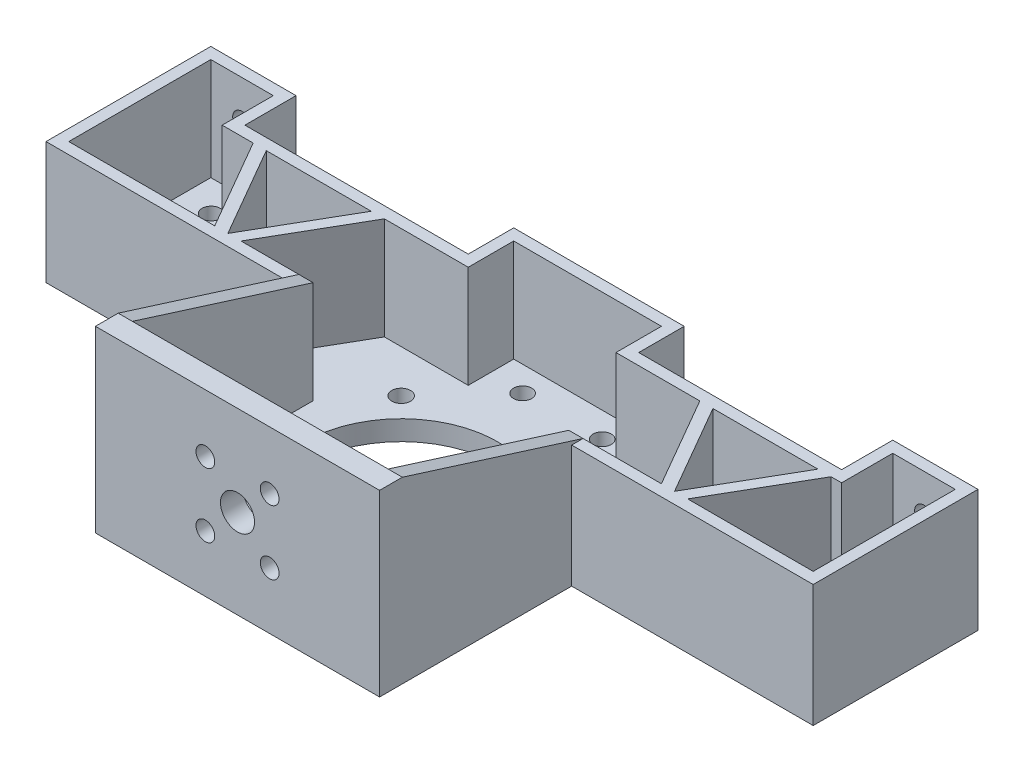
SolidWorks part; units mm, degrees
ref_plane "前视基准面" through (0, 0, 0) normal (0, 0, 1) x (1, 0, 0)
ref_plane "上视基准面" through (0, 0, 0) normal (0, 1, 0) x (1, 0, 0)
ref_plane "右视基准面" through (0, 0, 0) normal (1, 0, 0) x (0, 0, -1)
sketch "草图2" plane through (0, 0, 0) normal (0, 1, 0) x (1, 0, 0)
  line L15 (-42.5, 33.8) -> (-42.5, 62.8)
  line L16 (-42.5, 62.8) -> (-27.5, 62.8)
  line L17 (-27.5, 62.8) -> (-27.5, 53.8)
  line L18 (-27.5, 53.8) -> (11.8, 53.8)
  line L19 (11.8, 53.8) -> (11.8, 61.8)
  line L20 (11.8, 61.8) -> (41.8, 61.8)
  line L21 (41.8, 61.8) -> (41.8, 53.8)
  line L22 (41.8, 53.8) -> (77.5, 53.8)
  line L23 (77.5, 53.8) -> (77.5, 62.8)
  line L24 (77.5, 62.8) -> (92.5, 62.8)
  line L25 (92.5, 62.8) -> (92.5, 33.8)
  line L27 (-42.5, 33.8) -> (0, 33.8)
  line L28 (0, 33.8) -> (0, 0)
  line L29 (0, 0) -> (50, 0)
  line L30 (50, 0) -> (50, 33.8)
  line L31 (50, 33.8) -> (92.5, 33.8)
  line L32 (25, -43.9837) -> (25, 32.7782) construction
  line L33 (85, 58.3) -> (85, -14.8283) construction
  line L34 (-35, 58.3) -> (-35, -33.736) construction
  line L35 (26.8, 66.1921) -> (26.8, -26.5769) construction
  circle A1 centre (-35, 55.365) radius 1.6
  circle A3 centre (85, 55.365) radius 1.6
  circle A6 centre (19.8, 55.365) radius 1.6
  circle A7 centre (33.8, 55.365) radius 1.6
  circle A10 centre (25, 28.8) radius 17
  circle A11 centre (40.5, 44.3) radius 1.65
  circle A12 centre (40.5, 13.3) radius 1.65
  circle A13 centre (9.5, 13.3) radius 1.65
  circle A14 centre (9.5, 44.3) radius 1.65
  point P0 (-35, 55.365)
  point P1 (85, 55.365)
  point P2 (85, 58.3)
  point P3 (-35, 58.3)
  point P4 (33.8, 55.365)
  point P6 (19.8, 55.365)
  point P50 (25, 28.8)
  dimension "D2" = 120
  dimension "D22" = 34
  dimension "D7" = 28.8
  dimension "D10" = 50
  dimension "D11" = 25
  dimension "D14" = 3.3
  dimension "D17" = 31
  dimension "D3" = 1
  dimension "D4" = 14
  dimension "D5" = 54.8
  dimension "D8" = 8
  dimension "D9" = 30
  dimension "D12" = 15
  dimension "D13" = 15
  dimension "D15" = 20
  dimension "D16" = 4
  dimension "D18" = 4.5
extrude "凸台-拉伸2" add sketch "草图2" along normal blind 3.5
sketch "草图6" plane through (0, 3.5, 0) normal (0, 1, 0) x (1, 0, 0)
  line L9 (25, 28.8) -> (25, -10.253) construction
  line L12 (11.8, 53.8) -> (-27.5, 53.8) construction
  line L13 (11.8, 61.8) -> (11.8, 53.8) construction
  line L14 (41.8, 61.8) -> (11.8, 61.8) construction
  line L15 (41.8, 53.8) -> (41.8, 61.8) construction
  line L16 (77.5, 53.8) -> (41.8, 53.8) construction
  line L17 (77.5, 62.8) -> (77.5, 53.8) construction
  line L18 (92.5, 62.8) -> (77.5, 62.8) construction
  line L19 (92.5, 33.8) -> (92.5, 62.8) construction
  line L20 (50, 33.8) -> (92.5, 33.8) construction
  line L21 (50, 0) -> (50, 33.8) construction
  line L22 (0, 0) -> (50, 0) construction
  line L23 (0, 33.8) -> (0, 0) construction
  line L24 (-42.5, 33.8) -> (0, 33.8) construction
  line L25 (-42.5, 62.8) -> (-42.5, 33.8) construction
  line L26 (-27.5, 53.8) -> (-27.5, 62.8) construction
  line L27 (-27.5, 62.8) -> (-42.5, 62.8) construction
  line L28 (11.8, 53.8) -> (-27.5, 53.8)
  line L29 (11.8, 61.8) -> (11.8, 53.8)
  line L30 (41.8, 61.8) -> (11.8, 61.8)
  line L31 (41.8, 53.8) -> (41.8, 61.8)
  line L32 (77.5, 53.8) -> (41.8, 53.8)
  line L33 (77.5, 62.8) -> (77.5, 53.8)
  line L34 (92.5, 62.8) -> (77.5, 62.8)
  line L35 (92.5, 33.8) -> (92.5, 62.8)
  line L36 (50, 33.8) -> (92.5, 33.8)
  line L37 (50, 0) -> (50, 33.8)
  line L38 (0, 0) -> (50, 0)
  line L39 (0, 33.8) -> (0, 0)
  line L40 (-42.5, 33.8) -> (0, 33.8)
  line L41 (-42.5, 62.8) -> (-42.5, 33.8)
  line L42 (-27.5, 53.8) -> (-27.5, 62.8)
  line L43 (-27.5, 62.8) -> (-42.5, 62.8)
  line L44 (13.8, 51.8) -> (-29.5, 51.8)
  line L45 (-29.5, 51.8) -> (-29.5, 60.8)
  line L46 (-29.5, 60.8) -> (-40.5, 60.8)
  line L47 (-40.5, 60.8) -> (-40.5, 35.8)
  line L48 (-40.5, 35.8) -> (2.5, 35.8)
  line L49 (2.5, 35.8) -> (2.5, 4)
  line L50 (2.5, 4) -> (47.5, 4)
  line L51 (47.5, 4) -> (47.5, 35.8)
  line L52 (47.5, 35.8) -> (90.5, 35.8)
  line L53 (90.5, 35.8) -> (90.5, 60.8)
  line L54 (90.5, 60.8) -> (79.5, 60.8)
  line L55 (79.5, 60.8) -> (79.5, 51.8)
  line L56 (79.5, 51.8) -> (39.8, 51.8)
  line L57 (39.8, 51.8) -> (39.8, 59.8)
  line L58 (39.8, 59.8) -> (13.8, 59.8)
  line L59 (13.8, 59.8) -> (13.8, 51.8)
  dimension "D1" = 4
  dimension "D2" = 2
  dimension "D3" = 2
  dimension "D4" = 2
  dimension "D5" = 2
  dimension "D6" = 2
  dimension "D7" = 2
  dimension "D8" = 2
  dimension "D9" = 2
  dimension "D10" = 2
  dimension "D11" = 2
  dimension "D12" = 2
  dimension "D13" = 2
  dimension "D14" = 2.5
  dimension "D15" = 2.5
  dimension "D16" = 2
extrude "凸台-拉伸3" add sketch "草图6" along normal blind 18
sketch "草图11" plane through (0, 21.5, 0) normal (0, 1, 0) x (1, 0, 0)
  line L0 (2.5, 35.8) -> (2.5, 4)
  line L1 (2.5, 4) -> (47.5, 4)
  line L2 (47.5, 4) -> (47.5, 35.8)
  line L3 (47.5, 35.8) -> (50, 35.8)
  line L4 (47.5, 35.8) -> (90.5, 35.8) construction
  line L5 (50, 35.8) -> (50, 0)
  line L6 (50, 0) -> (50, 33.8) construction
  line L7 (50, 0) -> (0, 0)
  line L8 (0, 0) -> (0, 35.8)
  line L9 (-40.5, 35.8) -> (2.5, 35.8) construction
  line L10 (0, 35.8) -> (2.5, 35.8)
extrude "凸台-拉伸4" add sketch "草图11" along normal blind 10
sketch "草图12" plane through (0, 0, 0) normal (-1, 0, 0) x (0, 0, 1)
  line L0 (-35.8, 21.5) -> (-4, 31.5)
  line L1 (-35.8, 31.5) -> (0, 31.5) construction
  line L2 (-4, 31.5) -> (-35.8, 31.5)
  line L3 (-35.8, 31.5) -> (-35.8, 21.5)
  line L4 (0, 31.5) -> (0, 0) construction
  dimension "D1" = 4
extrude "切除-拉伸5" cut sketch "草图12" against normal through all
sketch "草图10" plane through (0, 0, 0) normal (0, 0, 1) x (1, 0, 0)
  line L0 (25, 37.2917) -> (25, -8.8083) construction
  line L5 (0, 0) -> (50, 0) construction
  line L6 (0, 31.5) -> (0, 0) construction
  line L7 (50, 31.5) -> (50, 0) construction
  circle A0 centre (25, 15.6569) radius 3
  circle A1 centre (30.6569, 21.3137) radius 1.65
  circle A2 centre (30.6569, 10) radius 1.65
  circle A3 centre (19.3431, 10) radius 1.65
  circle A4 centre (19.3431, 21.3137) radius 1.65
  point P2 (0, 0)
  point P19 (25, 15.6569)
  dimension "D1" = 10
  dimension "D2" = 6
  dimension "D3" = 3.3
  dimension "D4" = 8
  dimension "D5" = 4
extrude "切除-拉伸4" cut sketch "草图10" against normal blind 5
sketch "草图13" plane through (0, 3.5, 0) normal (0, 1, 0) x (1, 0, 0)
  line L0 (-21.7376, 51.8) -> (-12.5, 35.8)
  line L1 (13.8, 51.8) -> (-29.5, 51.8) construction
  line L2 (-40.5, 35.8) -> (0, 35.8) construction
  line L3 (-12.5, 35.8) -> (-3.2624, 51.8)
  line L5 (-21.7376, 51.8) -> (-24.047, 51.8)
  line L6 (13.8, 51.8) -> (-29.5, 51.8) construction
  line L7 (-24.047, 51.8) -> (-14.8094, 35.8)
  line L8 (-27.5, 53.8) -> (-27.5, 62.8) construction
  line L9 (-14.8094, 35.8) -> (-12.5, 35.8)
  line L10 (-3.2624, 51.8) -> (-0.953, 51.8)
  line L11 (-0.953, 51.8) -> (-10.1906, 35.8)
  line L12 (-10.1906, 35.8) -> (-12.5, 35.8)
  line L13 (-12.5, 35.8) -> (-12.5, 56.0294) construction
  line L14 (0, 35.8) -> (0, 4) construction
  line L15 (26.8, 61.8) -> (26.8, -17.4304) construction
  line L16 (41.8, 61.8) -> (11.8, 61.8) construction
  line L17 (63.7906, 35.8) -> (66.1, 35.8)
  line L18 (54.553, 51.8) -> (63.7906, 35.8)
  line L19 (56.8624, 51.8) -> (54.553, 51.8)
  line L20 (66.1, 35.8) -> (56.8624, 51.8)
  line L21 (68.4094, 35.8) -> (66.1, 35.8)
  line L22 (77.647, 51.8) -> (68.4094, 35.8)
  line L23 (75.3376, 51.8) -> (77.647, 51.8)
  line L24 (75.3376, 51.8) -> (66.1, 35.8)
  line M13 (13.8, 51.8) -> (-29.5, 51.8)
  line M17 (-40.5, 35.8) -> (2.5, 35.8)
  line M21 (47.5, 35.8) -> (90.5, 35.8)
  line M25 (79.5, 51.8) -> (39.8, 51.8)
  dimension "D1" = 2
  dimension "D2" = 60
  dimension "D3" = 15
  dimension "D4" = 12.5
extrude "凸台-拉伸5" add sketch "草图13" along normal up to surface (18 mm away) contours L7 L0 M13 M17 | L11 L3 M13 M17 | L20 L18 M21 M25 | L24 L22 M25 M21 up to face at (25.5143, 21.5, -51.3714)
sketch "草图14" plane through (0, 0, -62.8) normal (0, 0, -1) x (-1, 0, 0)
  line L0 (-25, 46.072) -> (-25, -18.623) construction
  line L1 (42.5, 21.5) -> (42.5, 0) construction
  line L2 (-92.5, 21.5) -> (-92.5, 0) construction
  line L3 (27.5, 0) -> (42.5, 0) construction
  circle A0 centre (35, 14.7) radius 1.65
  circle A1 centre (-85, 14.7) radius 1.65
  dimension "D1" = 3.3
  dimension "D2" = 120
  dimension "D3" = 14.7
extrude "切除-拉伸6" cut sketch "草图14" against normal blind 10
sketch "草图16" plane through (0, 0, 0) normal (-1, 0, 0) x (0, 0, 1)
  line L0 (-19.8, 26.5314) -> (-19.8, 18.5)
  line L1 (-35.8, 21.5) -> (-4, 31.5) construction
  line L2 (-19.8, 18.5) -> (-35.8, 18.5)
  line L3 (-35.8, 21.5) -> (-35.8, 18.5)
  line L4 (-35.8, 21.5) -> (-19.8, 26.5314)
  dimension "D1" = 16
  dimension "D2" = 3
